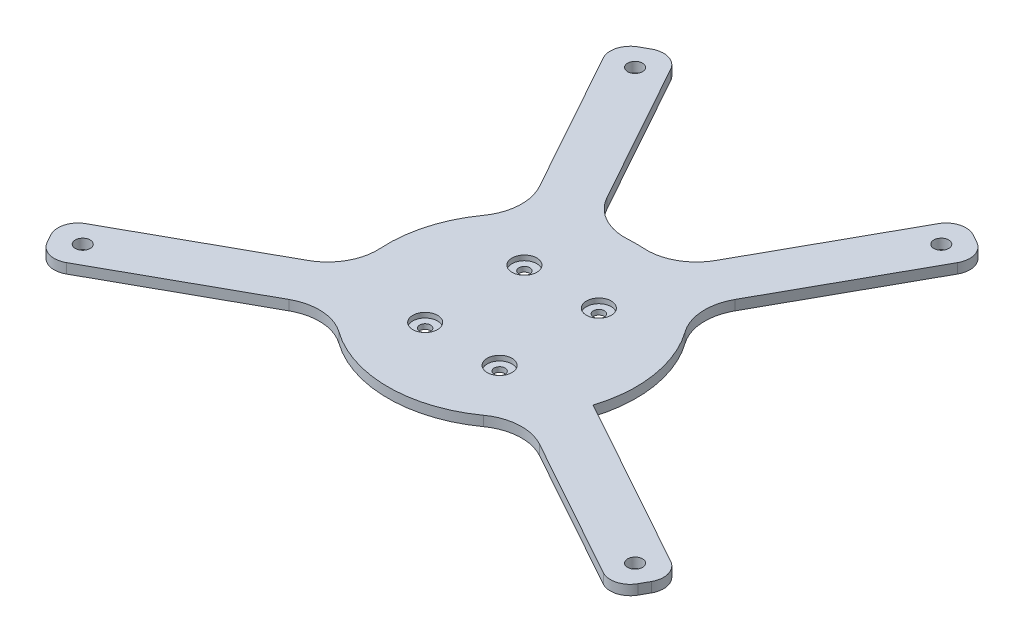
SolidWorks part; units mm, degrees
ref_plane "Front Plane" through (0, 0, 0) normal (0, 0, 1) x (1, 0, 0)
ref_plane "Top Plane" through (0, 0, 0) normal (0, 1, 0) x (1, 0, 0)
ref_plane "Right Plane" through (0, 0, 0) normal (1, 0, 0) x (0, 0, -1)
sketch "Sketch1" plane through (0, 0, 0) normal (0, 1, 0) x (1, 0, 0)
  circle A0 centre (0, 0) radius 25
  circle A1 centre (-7.5, 10) radius 1.1
  circle A2 centre (7.5, 10) radius 1.1
  circle A3 centre (-7.5, -10) radius 1.1
  circle A4 centre (7.5, -10) radius 1.1
  point P11 (-9.2598, 9.9224)
  point P12 (7.5, -10)
  dimension "D7" = 2.2
  dimension "D8" = 2.2
  dimension "D9" = 2.2
  dimension "D10" = 2.2
  dimension "D11" = 50
  dimension "D1" = 20
  dimension "D2" = 20
  dimension "D3" = 15
  dimension "D4" = 15
  dimension "D5" = 10
  dimension "D6" = 7.5
extrude "Boss-Extrude1" add sketch "Sketch1" along normal blind 2
sketch "Sketch2" plane through (0, 2, 0) normal (0, 1, 0) x (1, 0, 0)
  circle A0 centre (-7.5, 10) radius 2.5
  circle A1 centre (7.5, 10) radius 2.5
  circle A2 centre (-7.5, -10) radius 2.5
  circle A3 centre (7.5, -10) radius 2.5
  dimension "D1" = 5
  dimension "D2" = 5
  dimension "D3" = 5
  dimension "D4" = 5
extrude "Cut-Extrude1" cut sketch "Sketch2" against normal blind 1
sketch "Sketch3" plane through (0, 0, 0) normal (0, 1, 0) x (1, 0, 0)
  line L0 (-7.5031, 23.8475) -> (-26.9618, 58.9488)
  line L1 (-32.3996, 60.5079) -> (-34.1488, 59.5382)
  line L2 (-35.7079, 54.1004) -> (-16.2492, 18.9991)
  line L3 (-58.9488, -26.9618) -> (-23.8475, -7.5031)
  line L4 (-60.5079, -32.3996) -> (-59.5382, -34.1488)
  line L5 (-54.1004, -35.7079) -> (-18.9991, -16.2492)
  line L6 (-55.65, -30.85) -> (-60.023, -33.2742) construction
  line L7 (-33.2742, 60.023) -> (-30.85, 55.65) construction
  line L8 (-30.85, 55.65) -> (0, 0) construction
  line L9 (-55.65, -30.85) -> (0, 0) construction
  line L10 (0, -55) -> (0, 55) construction
  line L11 (60.5079, -32.3996) -> (59.5382, -34.1488)
  line L12 (58.9488, -26.9618) -> (23.8475, -7.5031)
  line L13 (54.1004, -35.7079) -> (18.9991, -16.2492)
  line L14 (32.3996, 60.5079) -> (34.1488, 59.5382)
  line L15 (7.5031, 23.8475) -> (26.9618, 58.9488)
  line L16 (35.7079, 54.1004) -> (16.2492, 18.9991)
  circle A0 centre (-30.85, 55.65) radius 1.5
  circle A1 centre (-55.65, -30.85) radius 1.5
  circle A2 centre (0, 0) radius 25 construction
  arc A3 (-7.5031, 23.8475) -> (-16.2492, 18.9991) centre (0, 0) ccw
  arc A4 (-23.8475, -7.5031) -> (-18.9991, -16.2492) centre (0, 0) ccw
  arc A5 (-59.5382, -34.1488) -> (-54.1004, -35.7079) centre (-56.0398, -32.2094) ccw
  arc A6 (-58.9488, -26.9618) -> (-60.5079, -32.3996) centre (-57.0094, -30.4602) ccw
  arc A7 (-34.1488, 59.5382) -> (-35.7079, 54.1004) centre (-32.2094, 56.0398) ccw
  arc A8 (-26.9618, 58.9488) -> (-32.3996, 60.5079) centre (-30.4602, 57.0094) ccw
  arc A9 (58.9488, -26.9618) -> (60.5079, -32.3996) centre (57.0094, -30.4602) cw
  arc A10 (23.8475, -7.5031) -> (18.9991, -16.2492) centre (0, 0) cw
  arc A11 (59.5382, -34.1488) -> (54.1004, -35.7079) centre (56.0398, -32.2094) cw
  arc A12 (26.9618, 58.9488) -> (32.3996, 60.5079) centre (30.4602, 57.0094) cw
  arc A13 (7.5031, 23.8475) -> (16.2492, 18.9991) centre (0, 0) cw
  arc A14 (34.1488, 59.5382) -> (35.7079, 54.1004) centre (32.2094, 56.0398) cw
  circle A15 centre (55.65, -30.85) radius 1.5
  circle A16 centre (30.85, 55.65) radius 1.5
  point P25 (-37.6472, 57.5988)
  point P28 (-28.9012, 62.4472)
  dimension "D5" = 3
  dimension "D6" = 3
  dimension "D11" = 4
  dimension "D12" = 4
  dimension "D1" = 55.65
  dimension "D2" = 30.85
  dimension "D3" = 55.65
  dimension "D4" = 30.85
  dimension "D7" = 5
  dimension "D8" = 10
  dimension "D9" = 10
  dimension "D10" = 5
extrude "Boss-Extrude2" add sketch "Sketch3" along normal up to surface (2 mm away) up to face at (7.5, 2, -7.5)
fillet "Fillet1" radius 10 6 edges at (-16.2492, 1, -18.9991) (-7.5031, 1, -23.8475) (16.2492, 1, -18.9991) (18.9991, 1, 16.2492) (-18.9991, 1, 16.2492) (-23.8475, 1, 7.5031)
fillet "Fillet2" radius 10 1 edges at (7.5031, 1, -23.8475)
